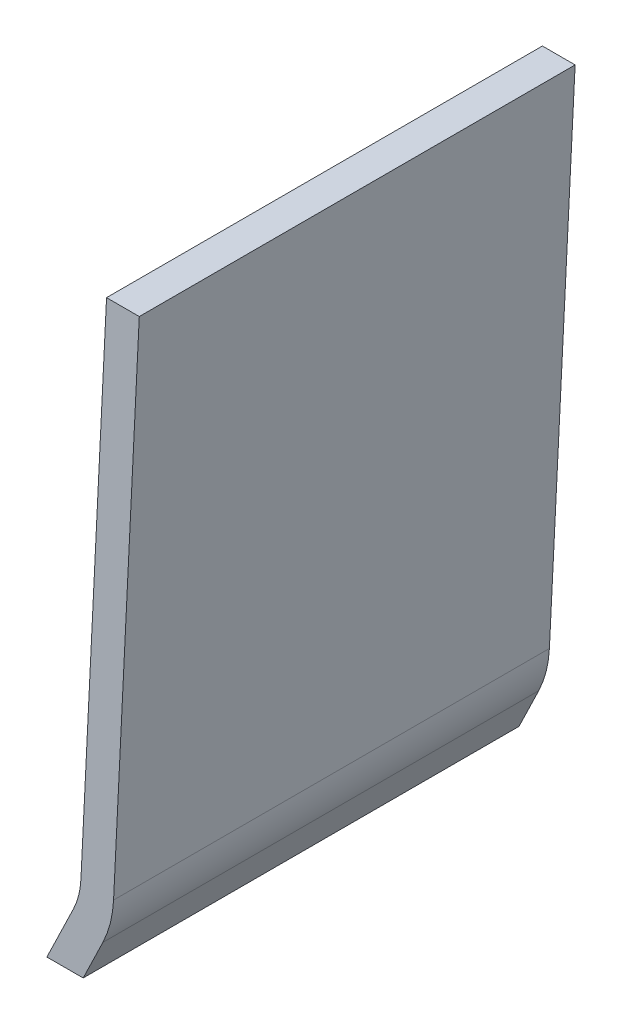
SolidWorks part; units mm, degrees
ref_plane "Front Plane" through (0, 0, 0) normal (0, 0, 1) x (1, 0, 0)
ref_plane "Top Plane" through (0, 0, 0) normal (0, 1, 0) x (1, 0, 0)
ref_plane "Right Plane" through (0, 0, 0) normal (1, 0, 0) x (0, 0, -1)
sketch "Sketch1" plane through (0, 0, 0) normal (0, 0, 1) x (1, 0, 0)
  line L0 (0, 0) -> (789.0246, 0) construction
  line L1 (530.8066, 551.4867) -> (560.8435, 551.4867)
  line L2 (509.361, 0) -> (527.3963, 37.2999)
  line L3 (537.2452, 75.875) -> (560.8435, 551.4867)
  line L4 (507.282, 77.3616) -> (530.8066, 551.4867)
  line L5 (500.3878, 50.3591) -> (476.0381, 0)
  line L6 (476.0381, 0) -> (509.361, 0)
  arc A0 (527.3963, 37.2999) -> (537.2452, 75.875) centre (437.368, 80.8305) ccw
  arc A1 (500.3878, 50.3591) -> (507.282, 77.3616) centre (437.368, 80.8305) ccw
  dimension "D2" = 100
  dimension "D1" = 70
  dimension "D3" = 30
  dimension "D4" = 30
extrude "Boss-Extrude1" add sketch "Sketch1" along normal blind 400
